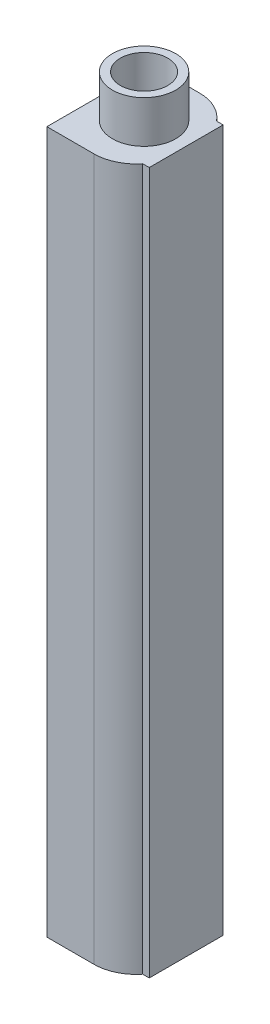
SolidWorks part; units mm, degrees
ref_plane "Front Plane" through (0, 0, 0) normal (0, 0, 1) x (1, 0, 0)
ref_plane "Top Plane" through (0, 0, 0) normal (0, 1, 0) x (1, 0, 0)
ref_plane "Right Plane" through (0, 0, 0) normal (1, 0, 0) x (0, 0, -1)
sketch "Sketch1" plane through (0, 0, 0) normal (0, 1, 0) x (1, 0, 0)
  line L0 (-16.415, 3) -> (-16.415, -17)
  line L1 (-16.415, -17) -> (-7.485, -17)
  line L3 (-1.24, -14) -> (0, -14)
  line L4 (0, -14) -> (0, 0)
  line L5 (0, 0) -> (-1.24, 0)
  line L7 (-16.415, 3) -> (-7.485, 3)
  arc A0 (-1.24, 0) -> (-7.485, 3) centre (-7.485, -5) ccw
  arc A1 (-1.24, -14) -> (-7.485, -17) centre (-7.485, -9) cw
  dimension "D2" = 8
  dimension "D3" = 8
  dimension "D1" = 20
  dimension "D4" = 8.93
  dimension "D5" = 14
  dimension "D6" = 1.24
extrude "Boss-Extrude1" add sketch "Sketch1" against normal blind 1.5
sketch "Sketch2" plane through (0, 0, 0) normal (0, 1, 0) x (1, 0, 0)
  line L6 (-16.415, 3) -> (-16.415, -17)
  line L7 (-16.415, -17) -> (-7.485, -17)
  line L8 (-1.24, -14) -> (0, -14)
  line L9 (0, -14) -> (0, 0)
  line L10 (0, 0) -> (-1.24, 0)
  line L11 (-7.485, 3) -> (-16.415, 3)
  line L12 (-7.485, 1.5) -> (-14.915, 1.5)
  line L13 (-14.915, 1.5) -> (-14.915, -15.5)
  line L14 (-14.915, -15.5) -> (-7.485, -15.5)
  line L15 (-2.0078, -12.5) -> (-1.5, -12.5)
  line L16 (-1.5, -12.5) -> (-1.5, -1.5)
  line L17 (-1.5, -1.5) -> (-2.0078, -1.5)
  line L18 (-7.485, 1.5) -> (-14.915, 1.5)
  line L19 (-14.915, 1.5) -> (-14.915, -15.5)
  line L20 (-14.915, -15.5) -> (-7.485, -15.5)
  line L21 (-2.0078, -12.5) -> (-1.5, -12.5)
  line L22 (-1.5, -12.5) -> (-1.5, -1.5)
  line L23 (-1.5, -1.5) -> (-2.0078, -1.5)
  arc A2 (-7.485, -17) -> (-1.24, -14) centre (-7.485, -9) ccw
  arc A3 (-1.24, 0) -> (-7.485, 3) centre (-7.485, -5) ccw
  arc A4 (-7.485, -15.5) -> (-2.0078, -12.5) centre (-7.485, -9) ccw
  arc A5 (-2.0078, -1.5) -> (-7.485, 1.5) centre (-7.485, -5) ccw
  arc A6 (-7.485, -15.5) -> (-2.0078, -12.5) centre (-7.485, -9) ccw
  arc A7 (-2.0078, -1.5) -> (-7.485, 1.5) centre (-7.485, -5) ccw
  dimension "D1" = 1.5
  dimension "D2" = 1.5
extrude "Boss-Extrude2" add sketch "Sketch2" along normal blind 131.6
sketch "Sketch3" plane through (0, 131.6, 0) normal (0, 1, 0) x (1, 0, 0)
  line L12 (-7.485, 3) -> (-16.415, 3)
  line L13 (-16.415, 3) -> (-16.415, -17)
  line L14 (-16.415, -17) -> (-7.485, -17)
  line L15 (-1.24, -14) -> (0, -14)
  line L16 (0, -14) -> (0, 0)
  line L17 (0, 0) -> (-1.24, 0)
  line L18 (-7.485, 3) -> (-16.415, 3)
  line L19 (-16.415, 3) -> (-16.415, -17)
  line L20 (-16.415, -17) -> (-7.485, -17)
  line L21 (-1.24, -14) -> (0, -14)
  line L22 (0, -14) -> (0, 0)
  line L23 (0, 0) -> (-1.24, 0)
  arc A4 (-7.485, -17) -> (-1.24, -14) centre (-7.485, -9) ccw
  arc A5 (-1.24, 0) -> (-7.485, 3) centre (-7.485, -5) ccw
  arc A6 (-7.485, -17) -> (-1.24, -14) centre (-7.485, -9) ccw
  arc A7 (-1.24, 0) -> (-7.485, 3) centre (-7.485, -5) ccw
  dimension "D1" = 0
extrude "Boss-Extrude3" add sketch "Sketch3" against normal blind 1.5
sketch "Sketch4" plane through (0, 131.6, 0) normal (0, 1, 0) x (1, 0, 0)
  line L0 (0, -14) -> (0, 0) construction
  line L1 (-16.415, -13.6525) -> (0, -13.6525) construction
  line L2 (-16.415, 3) -> (-16.415, -17) construction
  circle A0 centre (-8.2075, -6.7804) radius 7.5 construction
  circle A2 centre (-8.2075, -6.7804) radius 6
  circle A3 centre (-8.2075, -6.7804) radius 4.5
  point P11 (-8.2075, -13.6525)
  dimension "D1" = 15
  dimension "D2" = 1.5
  dimension "D3" = 1.5
extrude "Boss-Extrude4" add sketch "Sketch4" along normal blind 8
sketch "Sketch6" plane through (0, 131.6, 0) normal (0, 1, 0) x (1, 0, 0)
  circle A2 centre (-8.2075, -6.7804) radius 4.5
  circle A3 centre (-8.2075, -6.7804) radius 4.5
  dimension "D1" = 0
extrude "Cut-Extrude2" cut sketch "Sketch6" against normal blind 8
